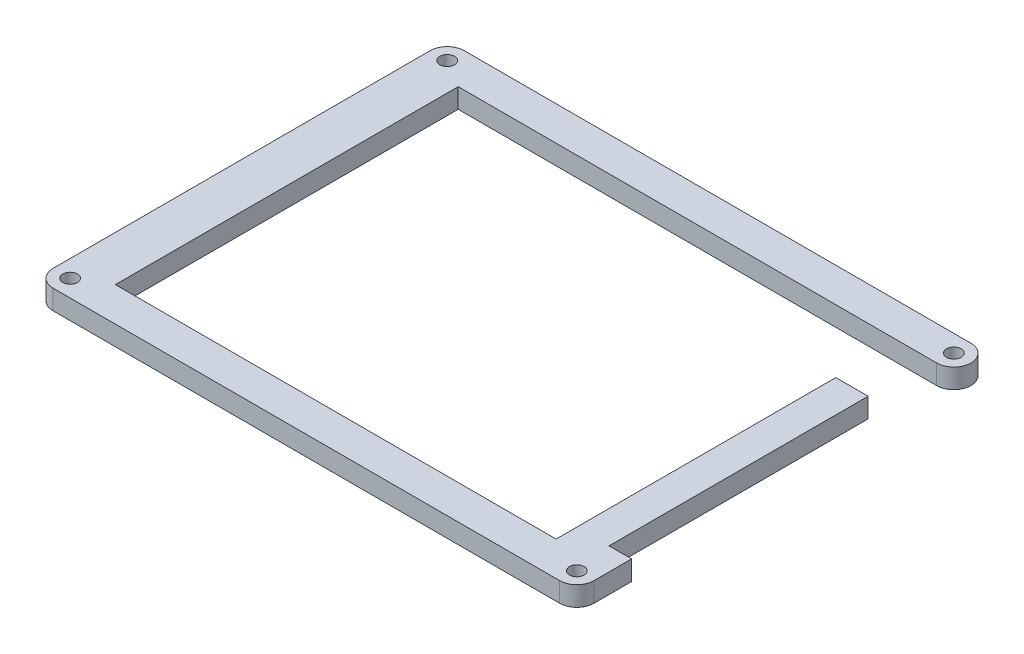
SolidWorks part; units mm, degrees
ref_plane "Front Plane" through (0, 0, 0) normal (0, 0, 1) x (1, 0, 0)
ref_plane "Top Plane" through (0, 0, 0) normal (0, 1, 0) x (1, 0, 0)
ref_plane "Right Plane" through (0, 0, 0) normal (1, 0, 0) x (0, 0, -1)
sketch "Sketch1" plane through (0, 0, 0) normal (0, 1, 0) x (1, 0, 0)
  line L0 (-40.9956, 2.7686) -> (40.9956, 2.7686)
  line L2 (40.9956, -2.7686) -> (-40.9956, -2.7686)
  arc A0 (-40.9956, 2.7686) -> (-40.9956, -2.7686) centre (-40.9956, 0) ccw
  arc A1 (40.9956, -2.7686) -> (40.9956, 2.7686) centre (40.9956, 0) ccw
  circle A2 centre (-40.9956, 0) radius 1.1938
  circle A3 centre (40.9956, 0) radius 1.1938
  dimension "D1" = 5.5372
  dimension "D2" = 5.5372
  dimension "D5" = 2.3876
  dimension "D6" = 2.3876
  dimension "D3" = 81.9912
  dimension "D4" = 40.9956
extrude "Boss-Extrude1" add sketch "Sketch1" along normal mid plane 3.175
sketch "Sketch2" plane through (0, 0, 0) normal (0, 1, 0) x (1, 0, 0)
  line L0 (-40.9956, -58.2422) -> (40.9956, -58.2422)
  line L1 (-43.7642, -1000) -> (-43.7642, 49000) construction
  line L2 (40.9956, -63.7794) -> (-40.9956, -63.7794)
  arc A0 (-40.9956, -58.2422) -> (-40.9956, -63.7794) centre (-40.9956, -61.0108) ccw
  arc A1 (40.9956, -63.7794) -> (40.9956, -58.2422) centre (40.9956, -61.0108) ccw
  circle A2 centre (-40.9956, -61.0108) radius 1.1938
  circle A3 centre (40.9956, -61.0108) radius 1.1938
  circle A4 centre (-40.9956, 0) radius 1.1938 construction
  circle A5 centre (40.9956, 0) radius 1.1938 construction
  arc A6 (-40.9956, 2.7686) -> (-40.9956, -2.7686) centre (-40.9956, 0) ccw construction
  point P19 (-43.7642, 0)
  dimension "D1" = 5.5372
  dimension "D2" = 5.5372
  dimension "D3" = 81.9912
  dimension "D4" = 61.0108
  dimension "D5" = 2.3876
  dimension "D6" = 2.3876
  dimension "D7" = 61.0108
extrude "Boss-Extrude2" add sketch "Sketch2" along normal mid plane 3.175 separate body
sketch "Sketch3" plane through (0, 1.5875, 0) normal (0, 1, 0) x (1, 0, 0)
  line L0 (-43.7642, 0) -> (-43.7642, -61.0108)
  line L1 (-36.4447, -2.7686) -> (-36.4447, -58.2422)
  line L2 (-40.9956, -2.7686) -> (40.9956, -2.7686) construction
  line L3 (40.9956, -58.2422) -> (-40.9956, -58.2422) construction
  line L4 (-36.4447, -2.7686) -> (-40.9956, -2.7686)
  line L5 (-40.9956, -58.2422) -> (-36.4447, -58.2422)
  arc A0 (-40.9956, 2.7686) -> (-40.9956, -2.7686) centre (-40.9956, 0) ccw construction
  arc A1 (-40.9956, -58.2422) -> (-40.9956, -63.7794) centre (-40.9956, -61.0108) ccw construction
  arc A2 (-40.9956, -2.7686) -> (-43.7642, 0) centre (-40.9956, 0) cw
  arc A3 (-43.7642, -61.0108) -> (-40.9956, -58.2422) centre (-40.9956, -61.0108) cw
  arc M2 (-40.9956, 2.7686) -> (-40.9956, -2.7686) centre (-40.9956, 0) ccw
  line M3 (-40.9956, -2.7686) -> (40.9956, -2.7686)
extrude "Boss-Extrude3" add sketch "Sketch3" against normal blind 3.175 contours L0 A3 L5 L1 M3 M2
sketch "Sketch4" plane through (0, 1.5875, 0) normal (0, 1, 0) x (1, 0, 0)
  line L0 (43.7642, -61.0108) -> (43.7642, -12.9794)
  line L1 (43.7642, -12.9794) -> (34.8742, -12.9794)
  line L2 (34.8742, -12.9794) -> (34.8742, -58.2422)
  line L3 (40.9956, -58.2422) -> (-36.4447, -58.2422) construction
  line L4 (-40.9956, -63.7794) -> (40.9956, -63.7794) construction
  line L5 (34.8742, -58.2422) -> (40.9956, -58.2422)
  arc A0 (40.9956, -63.7794) -> (40.9956, -58.2422) centre (40.9956, -61.0108) ccw construction
  arc A1 (40.9956, -58.2422) -> (43.7642, -61.0108) centre (40.9956, -61.0108) cw
  line M1 (40.9956, -58.2422) -> (-36.4447, -58.2422)
  arc M10 (40.9956, -63.7794) -> (40.9956, -58.2422) centre (40.9956, -61.0108) ccw
  dimension "D1" = 50.8
  dimension "D2" = 8.89
extrude "Boss-Extrude4" add sketch "Sketch4" against normal blind 3.175 contours L1 L2 L0 M1 M10
sketch "Sketch5" plane through (0, 1.5875, 0) normal (0, 1, 0) x (1, 0, 0)
  line L1 (43.7642, -12.9794) -> (40.108, -12.9794)
  line L2 (43.7642, -12.9794) -> (43.7642, -54.9128)
  line L3 (43.7642, -54.9128) -> (40.108, -54.9128)
  line L4 (40.108, -12.9794) -> (40.108, -54.9128)
extrude "Cut-Extrude1" cut sketch "Sketch5" against normal through all
equation "\"D4@Sketch1\"=.5*\"D3@Sketch1\""
